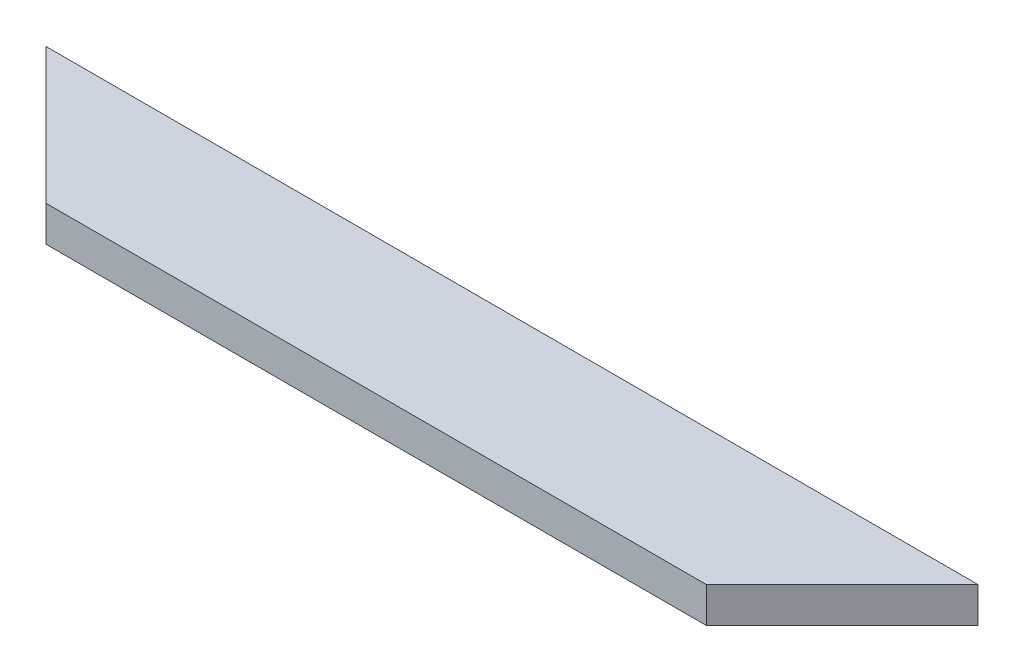
SolidWorks part; units mm, degrees
material "Pine"
ref_plane "Front Plane" through (0, 0, 0) normal (0, 0, 1) x (1, 0, 0)
ref_plane "Top Plane" through (0, 0, 0) normal (0, 1, 0) x (1, 0, 0)
ref_plane "Right Plane" through (0, 0, 0) normal (1, 0, 0) x (0, 0, -1)
sketch "Sketch1" plane through (0, 0, 0) normal (0, 1, 0) x (1, 0, 0)
  line L0 (0, 0) -> (-239.7125, 0)
  line L3 (-239.7125, 0) -> (-169.8625, -69.85)
  line L4 (-169.8625, -69.85) -> (0, -69.85)
  line L5 (0, -69.85) -> (0, 0)
  dimension "D1" = 169.8625
  dimension "D2" = 45
  dimension "D3" = 69.85
extrude "Boss-Extrude1" add sketch "Sketch1" along normal blind 18.2562
mirror "Mirror1" about plane through (0, 0, 0) normal (1, 0, 0) of "Boss-Extrude1"
